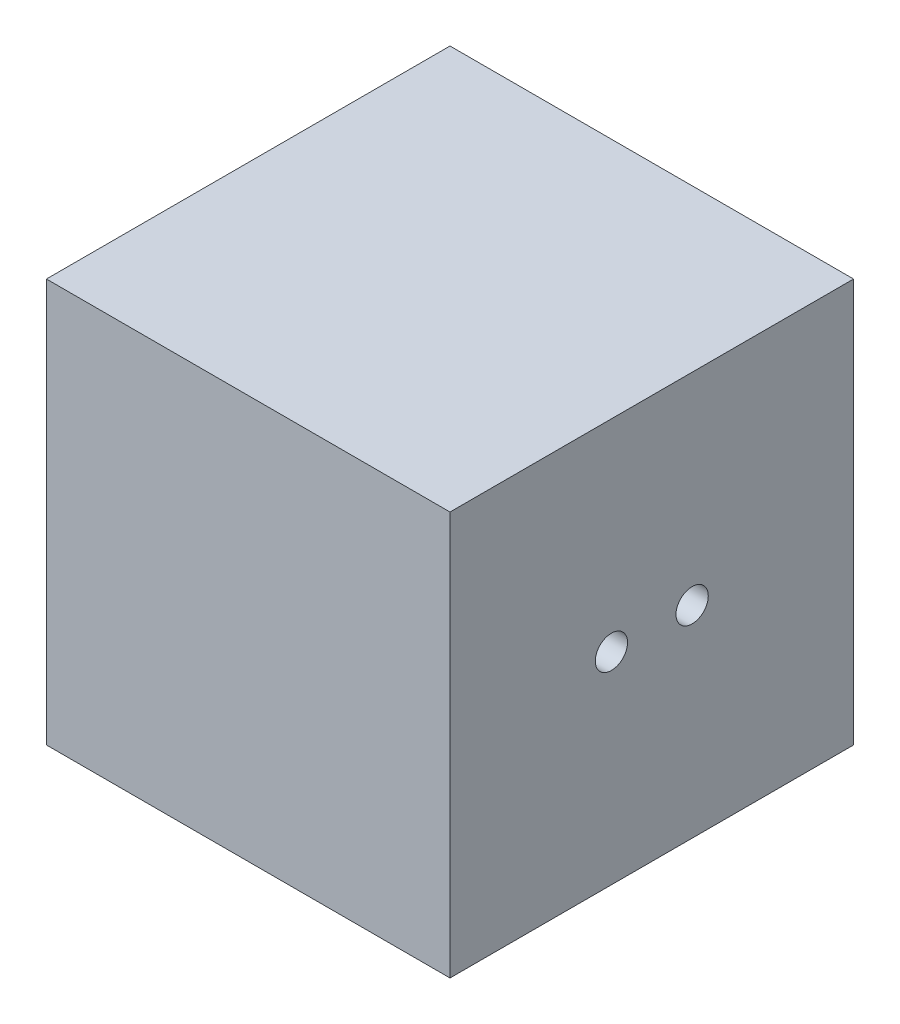
SolidWorks part; units mm, degrees
ref_plane "Plano frontal" through (0, 0, 0) normal (0, 0, 1) x (1, 0, 0)
ref_plane "Plano superior" through (0, 0, 0) normal (0, 1, 0) x (1, 0, 0)
ref_plane "Plano direito" through (0, 0, 0) normal (1, 0, 0) x (0, 0, -1)
sketch "Esboço1" plane through (0, 0, 0) normal (0, 0, 1) x (1, 0, 0)
  line L1 (-50, -50) -> (50, -50)
  line L2 (-50, -50) -> (-50, 50)
  line L3 (-50, 50) -> (50, 50)
  line L4 (50, -50) -> (50, 50)
  line L5 (0, 50) -> (0, -50) construction
  line L6 (-50, 0) -> (50, 0) construction
  point P0 (0, 0)
extrude "Ressalto-extrusão1" add sketch "Esboço1" along normal blind 100
sketch "Esboço2" plane through (50, 0, 0) normal (1, 0, 0) x (0, 0, -1)
  circle A0 centre (-40, 0) radius 4
  circle A1 centre (-60, 0) radius 4
extrude "Corte-extrusão1" cut sketch "Esboço2" against normal up to next
sketch "Esboço3" plane through (0, -50, 0) normal (0, -1, 0) x (-1, 0, 0)
  circle A0 centre (0, -50) radius 7
  circle A1 centre (0, -25) radius 1.7
  circle A2 centre (21.6506, -62.5) radius 1.7
  circle A3 centre (-21.6506, -62.5) radius 1.7
  point P10 (0, -50)
  dimension "D1" = 3
extrude "Corte-extrusão2" cut sketch "Esboço3" against normal blind 10
